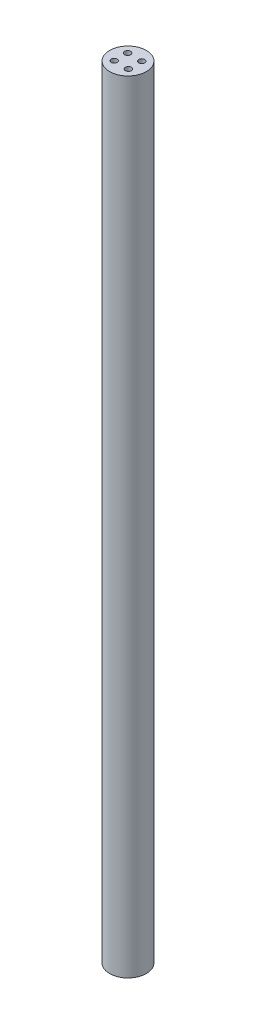
SolidWorks part; units mm, degrees
ref_plane "Front Plane" through (0, 0, 0) normal (0, 0, 1) x (1, 0, 0)
ref_plane "Top Plane" through (0, 0, 0) normal (0, 1, 0) x (1, 0, 0)
ref_plane "Right Plane" through (0, 0, 0) normal (1, 0, 0) x (0, 0, -1)
sketch "Sketch1" plane through (0, 0, 0) normal (0, 1, 0) x (1, 0, 0)
  circle A0 centre (0, 0) radius 2.3876
  dimension "D1" = 4.7752
extrude "Boss-Extrude1" add sketch "Sketch1" along normal blind 101.6
sketch "Sketch2" plane through (0, 101.6, 0) normal (0, 1, 0) x (1, 0, 0)
  circle A0 centre (-0.9235, 0.8718) radius 0.3937
  circle A1 centre (0.9235, 0.8718) radius 0.3937
  circle A2 centre (0.9235, -0.8718) radius 0.3937
  circle A3 centre (-0.9235, -0.8718) radius 0.3937
  circle A4 centre (0, 0) radius 2.3876 construction
  dimension "D1" = 0.7874
  dimension "D5" = 0.9235
  dimension "D2" = 1.27
  dimension "D3" = 1.27
  dimension "D4" = 1.27
extrude "Cut-Extrude1" cut sketch "Sketch2" against normal through all
